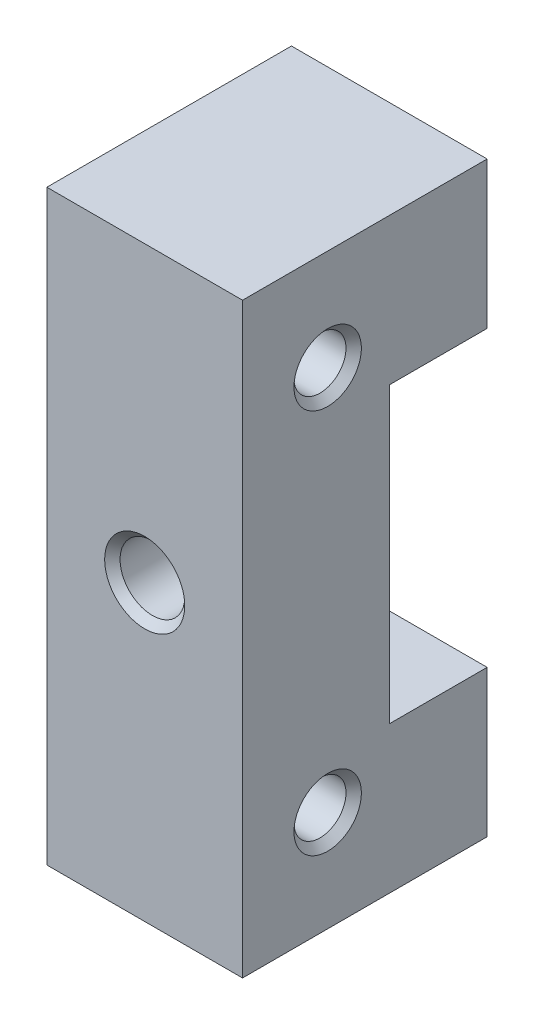
SolidWorks part; units mm, degrees
material "6061 Alloy"
ref_plane "Front Plane" through (0, 0, 0) normal (0, 0, 1) x (1, 0, 0)
ref_plane "Top Plane" through (0, 0, 0) normal (0, 1, 0) x (1, 0, 0)
ref_plane "Right Plane" through (0, 0, 0) normal (1, 0, 0) x (0, 0, -1)
sketch "Sketch1" plane through (0, 0, 0) normal (1, 0, 0) x (0, 0, -1)
  line L0 (-44.45, 241.3) -> (-12.7, 241.3) construction
  line L1 (-12.7, 241.3) -> (-12.7, 260.35) construction
  line L2 (-12.7, 260.35) -> (-25.4, 260.35) construction
  line L3 (-25.4, 260.35) -> (-25.4, 298.45) construction
  line L4 (-12.7, 298.45) -> (-12.7, 317.5) construction
  line L5 (-25.4, 298.45) -> (-12.7, 298.45) construction
  line L6 (-44.45, 317.5) -> (-44.45, 241.3) construction
  line L7 (-12.7, 317.5) -> (-44.45, 317.5) construction
  line L8 (-44.45, 241.3) -> (-12.7, 241.3)
  line L9 (-12.7, 241.3) -> (-12.7, 260.35)
  line L10 (-12.7, 260.35) -> (-25.4, 260.35)
  line L11 (-25.4, 260.35) -> (-25.4, 298.45)
  line L12 (-12.7, 298.45) -> (-12.7, 317.5)
  line L13 (-25.4, 298.45) -> (-12.7, 298.45)
  line L14 (-44.45, 317.5) -> (-44.45, 241.3)
  line L15 (-12.7, 317.5) -> (-44.45, 317.5)
  line L16 (-12.7, 298.45) -> (-12.7, 260.35) construction
  line L17 (-12.7, 279.4) -> (-25.4, 279.4) construction
  line L18 (-25.4, 279.4) -> (-44.45, 279.4) construction
  line L19 (-33.4, 304.4) -> (-33.4, 254.4) construction
  point P13 (-33.4, 279.4)
  dimension "D1" = 50
  dimension "D2" = 8
extrude "Boss-Extrude1" add sketch "Sketch1" along normal mid plane 25.4
sketch "Sketch4" plane through (12.7, 0, 0) normal (1, 0, 0) x (0, 0, -1)
  point P0 (-33.4, 304.4)
  point P3 (-33.4, 254.4)
hole_wizard "1/4 Clearance Hole1" positions "Sketch4" profile "Sketch3" hole size "1/4" standard "ANSI Inch" end condition through all
sketch "Sketch3" plane through (12.7, 304.4, 33.4) normal (0, 1, 0) x (0, 0, -1)
  line L0 (0, 0) -> (0, 25.4)
  line L1 (0, 25.4) -> (3.3782, 25.4)
  line L2 (3.3782, 25.4) -> (3.3782, 0)
  line L5 (3.3782, 0) -> (0, 0)
  line L11 (0, -6.35) -> (0, 107.95) construction
  dimension "Thru Hole Dia." = 6.7564
  dimension "Thru Hole Depth" = 25.4
sketch "Sketch7" plane through (0, 0, 25.4) normal (0, 0, -1) x (-1, 0, 0)
  line L0 (0, 317.5) -> (0, 241.3) construction
  point P0 (0, 279.4)
  point P7 (0, 279.4)
hole_wizard "M8 Clearance Hole1" positions "Sketch7" profile "Sketch6" hole size "M8" standard "ANSI Metric" end condition through all
sketch "Sketch6" plane through (0, 279.4, 25.4) normal (1, 0, 0) x (0, 1, 0)
  line L0 (0, 0) -> (0, 19.05)
  line L1 (0, 19.05) -> (4.2, 19.05)
  line L2 (4.2, 19.05) -> (4.2, 0)
  line L5 (4.2, 0) -> (0, 0)
  line L11 (0, -6.35) -> (0, 107.95) construction
  dimension "Thru Hole Dia." = 8.4
  dimension "Thru Hole Depth" = 19.05
chamfer "Chamfer1" distance 1 angle 45 6 edges at (-4.2, 279.4, 25.4) (-4.2, 279.4, 44.45) (12.7, 254.4, 30.0218) (-12.7, 254.4, 30.0218) (12.7, 304.4, 30.0218) (-12.7, 304.4, 30.0218)
